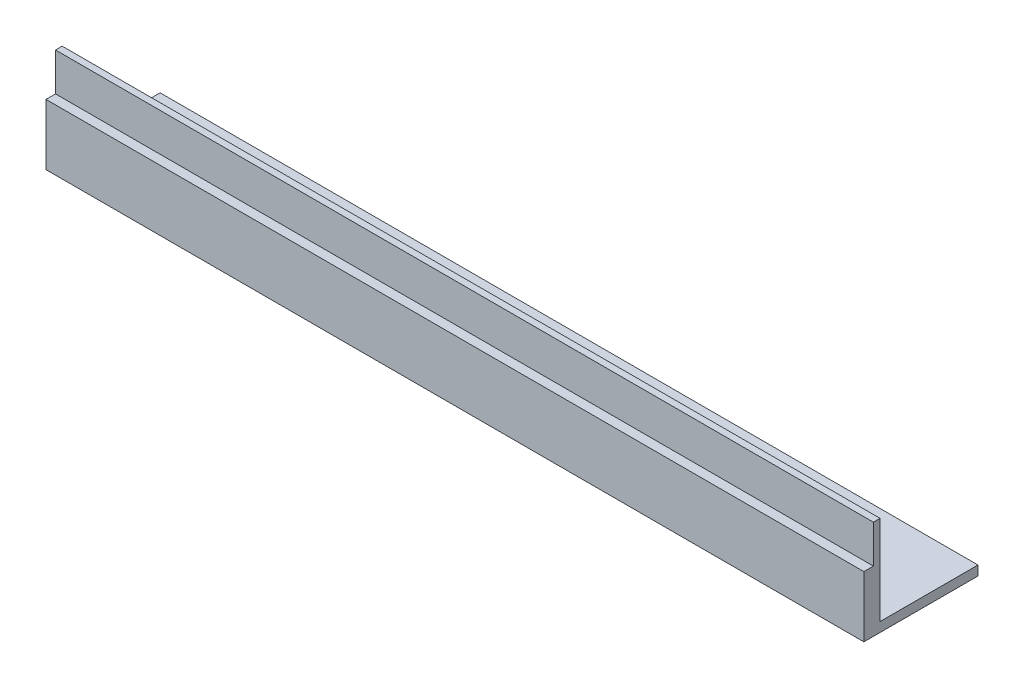
SolidWorks part; units mm, degrees
ref_plane "Front Plane" through (0, 0, 0) normal (0, 0, 1) x (1, 0, 0)
ref_plane "Top Plane" through (0, 0, 0) normal (0, 1, 0) x (1, 0, 0)
ref_plane "Right Plane" through (0, 0, 0) normal (1, 0, 0) x (0, 0, -1)
sketch "Sketch2" plane through (0, 0, 0) normal (1, 0, 0) x (0, 0, -1)
  line L0 (-30, 1.75) -> (-27.5, 1.75)
  line L1 (-30, -14.25) -> (30, -14.25)
  line L2 (-30, -14.25) -> (-30, 14.25)
  line L3 (-30, 14.25) -> (30, 14.25)
  line L4 (30, -14.25) -> (30, 14.25)
  line L5 (-30, -14.25) -> (30, 14.25) construction
  line L6 (-30, 14.25) -> (30, -14.25) construction
  line L7 (-25.75, -11.75) -> (25.75, -11.75)
  line L8 (-25.75, -11.75) -> (-25.75, 11.75)
  line L9 (-25.75, 11.75) -> (25.75, 11.75)
  line L10 (25.75, -11.75) -> (25.75, 11.75)
  line L11 (-25.75, -11.75) -> (25.75, 11.75) construction
  line L12 (-25.75, 11.75) -> (25.75, -11.75) construction
  line L13 (-27.5, 1.75) -> (-27.5, 11.75)
  line L14 (-27.5, 11.75) -> (-25.75, 11.75)
  line L15 (0, -14.25) -> (0, 14.25)
  line L16 (-27.5, 9.25) -> (-30, 11.75)
  line L17 (-30, 11.75) -> (-27.5, 11.75)
  line L18 (-27.5, 11.75) -> (-25.75, 11.75)
  point P0 (0, 0)
  point P5 (0, 0)
  dimension "D1" = 60
  dimension "D2" = 28.5
  dimension "D3" = 51.5
  dimension "D4" = 23.5
  dimension "D5" = 2.5
  dimension "D6" = 10
  dimension "D7" = 45
extrude "Boss-Extrude1" add sketch "Sketch2" along normal blind 215 contours L1 L15 L7 L8 L14 L13 L0 L2
